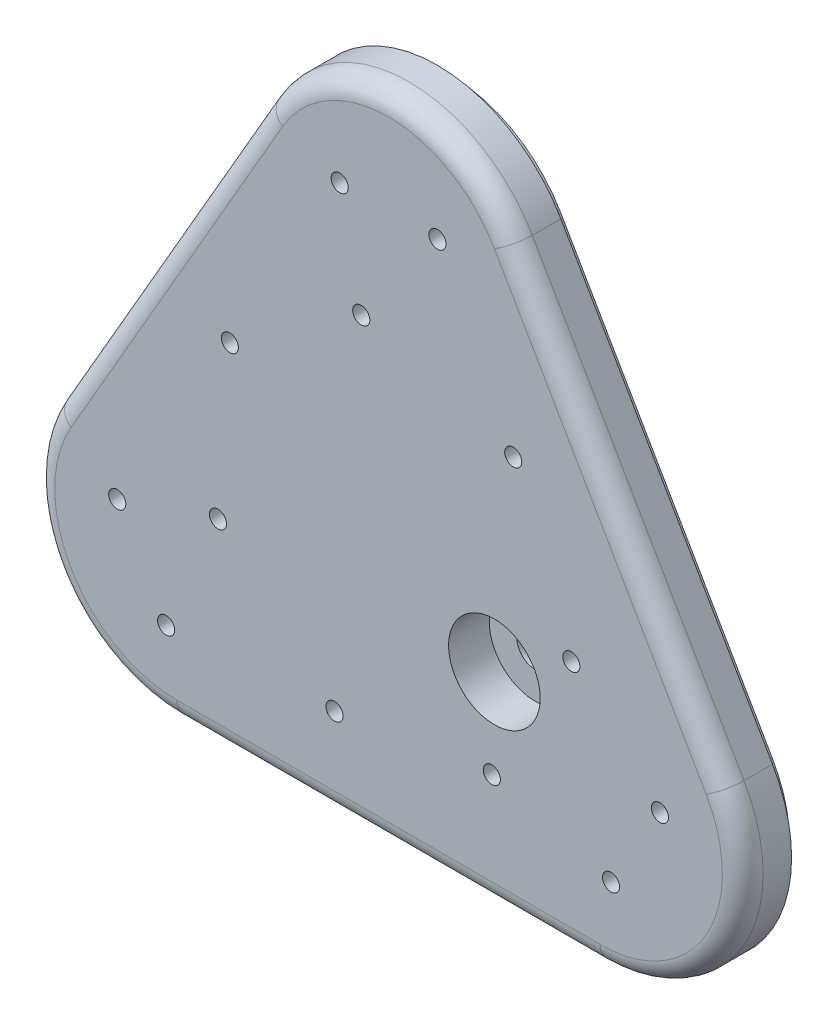
SolidWorks part; units mm, degrees
ref_plane "Plano frontal" through (0, 0, 0) normal (0, 0, 1) x (1, 0, 0)
ref_plane "Plano superior" through (0, 0, 0) normal (0, 1, 0) x (1, 0, 0)
ref_plane "Plano direito" through (0, 0, 0) normal (1, 0, 0) x (0, 0, -1)
sketch "Esboço1" plane through (0, 0, 0) normal (0, 0, 1) x (1, 0, 0)
  line L0 (0, 0) -> (0, 60) construction
  line L1 (0, 0) -> (-51.9615, -30) construction
  line L2 (0, 0) -> (51.9615, -30) construction
  line L3 (0, 0) -> (0, -52.5079) construction
  line L4 (0, 0) -> (45.4731, 26.2539) construction
  line L5 (0, 0) -> (-45.4731, 26.2539) construction
  line L6 (-12, 70) -> (12, 70) construction
  line L7 (-66.6218, -24.6077) -> (-54.6218, -45.3923) construction
  line L8 (-51.9615, -30) -> (-60.6218, -35) construction
  line L9 (0, 60) -> (0, 70) construction
  line L10 (51.9615, -30) -> (60.6218, -35) construction
  line L11 (54.6218, -45.3923) -> (66.6218, -24.6077) construction
  line L12 (31.8335, -36.8427) -> (39.8285, -22.995) construction
  line L13 (47.8235, -9.1473) -> (39.8285, -22.995) construction
  line L14 (-30.3109, 77.5) -> (-82.2724, -12.5)
  line L15 (30.3109, 77.5) -> (82.2724, -12.5)
  line L16 (-51.9615, -65) -> (51.9615, -65)
  arc A1 (51.9615, -65) -> (82.2724, -12.5) centre (51.9615, -30) ccw
  arc A2 (30.3109, 77.5) -> (-30.3109, 77.5) centre (0, 60) ccw
  arc A3 (-82.2724, -12.5) -> (-51.9615, -65) centre (-51.9615, -30) ccw
  circle A10 centre (-12, 70) radius 2.1
  circle A11 centre (-66.6218, -24.6077) radius 2.1
  circle A12 centre (12, 70) radius 2.1
  circle A13 centre (-54.6218, -45.3923) radius 2.1
  circle A24 centre (66.6218, -24.6077) radius 2.1
  circle A25 centre (54.6218, -45.3923) radius 2.1
  circle A27 centre (25.9808, -15) radius 4.5
  point P25 (0, 70)
  point P40 (51.9615, -30)
  point P41 (51.9615, -30)
  point P45 (60.6218, -35)
  point P53 (25.9808, -15)
  dimension "D3" = 9
  dimension "D5" = 70
  dimension "D9" = 4.2
  dimension "D10" = 12
  dimension "D11" = 12
  dimension "D12" = 10
  dimension "D13" = 70
  dimension "D14" = 30
  dimension "D16" = 15.99
  dimension "D17" = 10
  dimension "D18" = 24
  dimension "D1" = 120
  dimension "D2" = 120
  dimension "D4" = 60
  dimension "D6" = 120
  dimension "D7" = 120
extrude "Ressalto-extrusão1" add sketch "Esboço1" along normal blind 15
sketch "Esboço2" plane through (0, 0, 0) normal (0, 0, -1) x (-1, 0, 0)
  line L0 (0, -65) -> (0, 0) construction
  line L1 (0, 0) -> (56.2917, 32.5) construction
  line L2 (0, 0) -> (-56.2917, 32.5) construction
  line L4 (51.9615, -65) -> (-51.9615, -65) construction
  line L5 (30.3109, 77.5) -> (82.2724, -12.5) construction
  line L6 (-82.2724, -12.5) -> (-30.3109, 77.5) construction
  circle A4 centre (38.9711, 22.5) radius 2.1
  circle A5 centre (41.8893, -16.4403) radius 2.1
  circle A6 centre (13.264, -43.0008) radius 2.1
  circle A7 centre (-25.3494, -37.1807) radius 2.1
  circle A8 centre (-44.8742, -3.3629) radius 2.1
  circle A9 centre (-30.6078, 32.9873) radius 2.1
  circle A10 centre (6.7069, 44.4974) radius 2.1
  point P31 (0, 0)
  dimension "D1" = 4.2
  dimension "D2" = 45
  dimension "D4" = 120
  dimension "D5" = 120
  dimension "D3" = 7
extrude "Corte-extrusão1" cut sketch "Esboço2" against normal up to surface (15 mm away) up to face at (30.4808, -15, 15)
sketch "Esboço4" plane through (0, 0, 0) normal (0, 0, -1) x (-1, 0, 0)
  line L0 (51.9615, -65) -> (-51.9615, -65) construction
  line L1 (30.3109, 77.5) -> (82.2724, -12.5) construction
  line L2 (-82.2724, -12.5) -> (-30.3109, 77.5) construction
  line L3 (51.9615, -65) -> (-51.9615, -65)
  line L4 (30.3109, 77.5) -> (82.2724, -12.5)
  line L5 (-82.2724, -12.5) -> (-30.3109, 77.5)
  line L9 (51.9615, -61.5) -> (-51.9615, -61.5)
  line L10 (-79.2413, -14.25) -> (-27.2798, 75.75)
  line L11 (27.2798, 75.75) -> (79.2413, -14.25)
  arc A0 (-82.2724, -12.5) -> (-51.9615, -65) centre (-51.9615, -30) ccw construction
  arc A1 (51.9615, -65) -> (82.2724, -12.5) centre (51.9615, -30) ccw construction
  arc A2 (30.3109, 77.5) -> (-30.3109, 77.5) centre (0, 60) ccw construction
  arc A3 (-82.2724, -12.5) -> (-51.9615, -65) centre (-51.9615, -30) ccw
  arc A4 (51.9615, -65) -> (82.2724, -12.5) centre (51.9615, -30) ccw
  arc A5 (30.3109, 77.5) -> (-30.3109, 77.5) centre (0, 60) ccw
  arc A9 (-79.2413, -14.25) -> (-51.9615, -61.5) centre (-51.9615, -30) ccw
  arc A10 (27.2798, 75.75) -> (-27.2798, 75.75) centre (0, 60) ccw
  arc A11 (51.9615, -61.5) -> (79.2413, -14.25) centre (51.9615, -30) ccw
  dimension "D1" = 3.5
extrude "Corte-extrusão2" cut sketch "Esboço4" against normal blind 3
sketch "Esboço5" plane through (0, 0, 15) normal (0, 0, 1) x (1, 0, 0)
  circle A0 centre (25.9808, -15) radius 11.25
  dimension "D1" = 22.5
extrude "Corte-extrusão3" cut sketch "Esboço5" against normal blind 10
fillet "Filete1" radius 5 6 edges at (0, 95, 15) (56.2917, 32.5, 15) (82.2724, -47.5, 15) (0, -65, 15) (-82.2724, -47.5, 15) (-56.2917, 32.5, 15)
